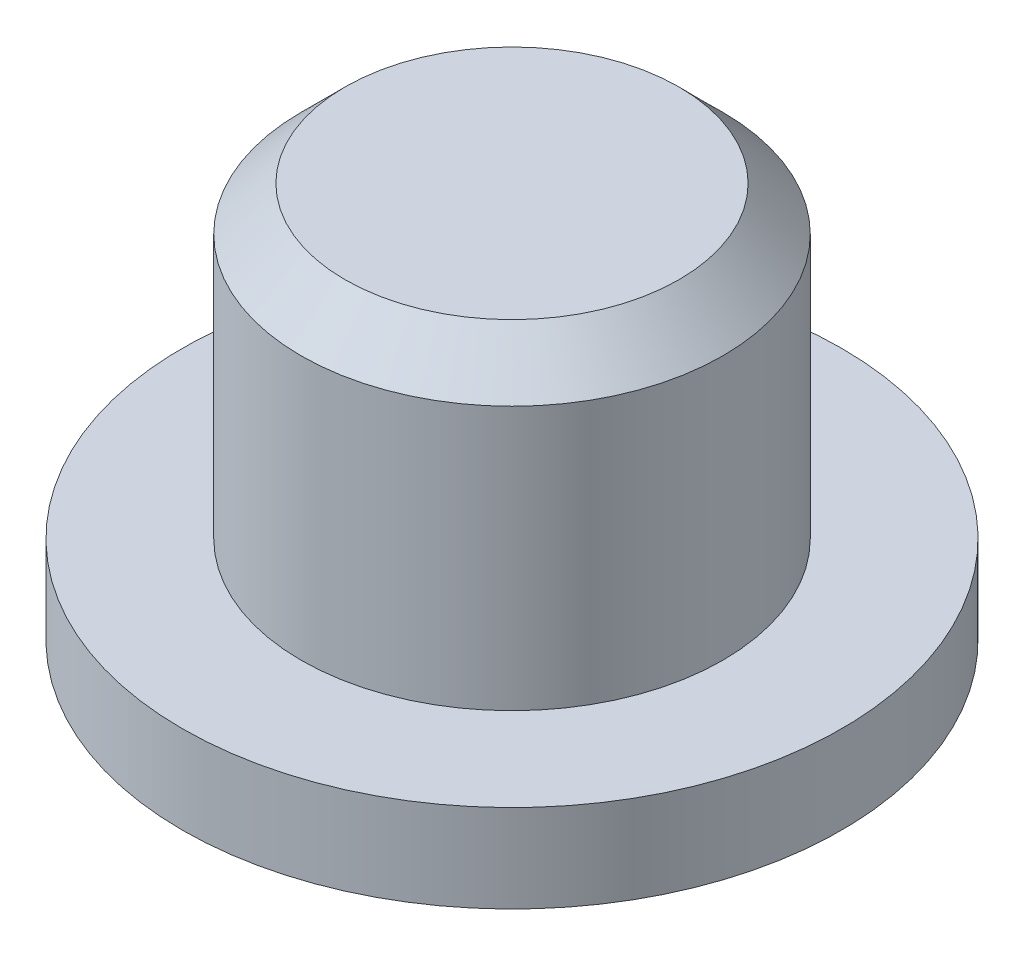
SolidWorks part; units mm, degrees
ref_plane "Front Plane" through (0, 0, 0) normal (0, 0, 1) x (1, 0, 0)
ref_plane "Top Plane" through (0, 0, 0) normal (0, 1, 0) x (1, 0, 0)
ref_plane "Right Plane" through (0, 0, 0) normal (1, 0, 0) x (0, 0, -1)
sketch "Sketch1" plane through (0, 0, 0) normal (0, 1, 0) x (1, 0, 0)
  circle A0 centre (0, 0) radius 4.8
extrude "Boss-Extrude1" add sketch "Sketch1" along normal blind 9
sketch "Sketch2" plane through (0, 0, 0) normal (0, -1, 0) x (1, 0, 0)
  circle A0 centre (0, 0) radius 7.5
extrude "Boss-Extrude2" add sketch "Sketch2" against normal blind 2
chamfer "Chamfer1" distance 1 angle 45 1 edges at (0, 9, 4.8)
